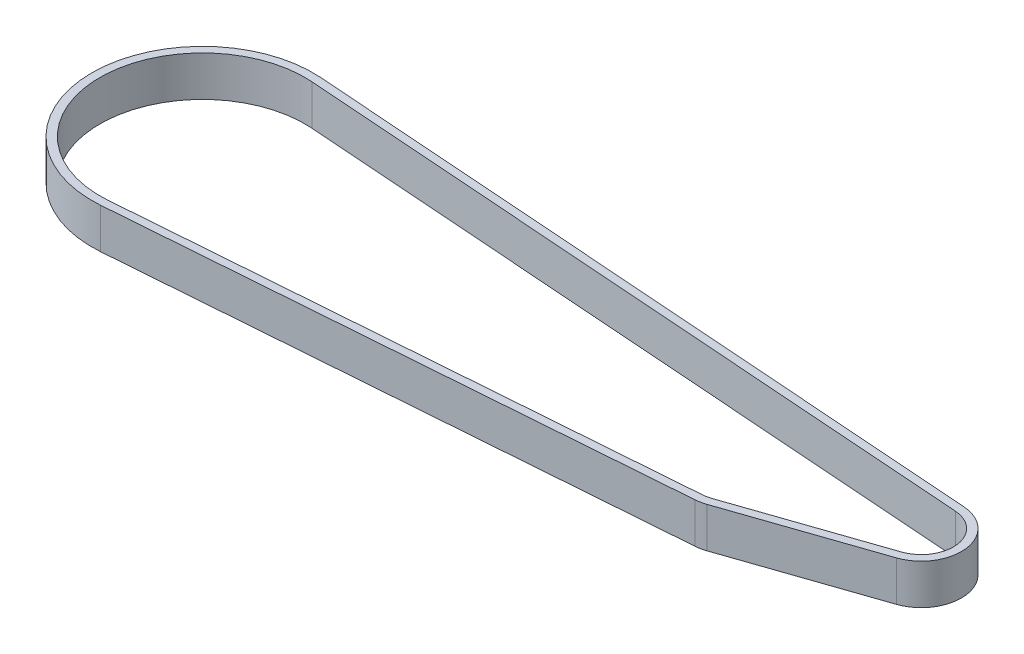
SolidWorks part; units mm, degrees
ref_plane "Alzado" through (0, 0, 0) normal (1, 0, 0) x (0, 1, 0)
ref_plane "Planta" through (0, 0, 0) normal (0, 0, 1) x (0, 1, 0)
ref_plane "Vista lateral" through (0, 0, 0) normal (0, 1, 0) x (-1, 0, 0)
sketch "Croquis1" plane through (0, 0, 0) normal (0, 1, 0) x (-1, 0, 0)
  line L0 (0, 0) -> (173.5, 0) construction
  line L2 (-0.5745, -7.9392) -> (171.6616, -20.4036)
  line L5 (34.3948, 19.937) -> (171.5635, 30.3963)
  line L6 (34.2427, 21.9312) -> (171.4114, 32.3905)
  line L8 (-0.7189, -9.934) -> (171.5172, -22.3984)
  line L9 (-2.5816, 7.5297) -> (32.4184, 19.5297)
  line L10 (-3.2303, 9.4216) -> (31.7697, 21.4216)
  line L11 (173.5, 0) -> (173.5, 5) construction
  line L12 (173.5, 5) -> (0, 0) construction
  arc A0 (-2.5816, 7.5297) -> (-0.5745, -7.9392) centre (0, 0) ccw
  arc A1 (171.6616, -20.4036) -> (171.5635, 30.3963) centre (173.5, 5) ccw
  arc A4 (34.3948, 19.937) -> (32.4184, 19.5297) centre (35, 12) ccw
  arc A6 (171.5172, -22.3984) -> (171.4114, 32.3905) centre (173.5, 5) ccw
  arc A7 (-3.2303, 9.4216) -> (-0.7189, -9.934) centre (0, 0) ccw
  arc A8 (34.2427, 21.9312) -> (31.7697, 21.4216) centre (35, 12) ccw
  arc A9 (171.6616, -20.4036) -> (171.5635, 30.3963) centre (173.5, 5) ccw construction
  dimension "D1" = 15.92
  dimension "D2" = 50.94
  dimension "D5" = 7.96
  dimension "D6" = 35
  dimension "D7" = 12
  dimension "D3" = 173.5
  dimension "D8" = 5
  dimension "D4" = 2
extrude "Saliente-Extruir1" add sketch "Croquis1" along normal mid plane 10
equation "\"Dp1\"=15.92"
equation "\"Dp2\"= 50.94"
equation "\"Lp\"= 455"
equation "\"e\"= 1"
equation "\"D1@Croquis1\"=\"Dp1\""
equation "\"D2@Croquis1\"=\"Dp2\""
equation "\"B\"= 10"
equation "\"D1@Saliente-Extruir1\"=\"B\""
equation "\"Dp_tensor\"=15.92"
equation "\"D5@Croquis1\"=\"Dp_tensor\"/2"
equation "\"x_tensora\"=35"
equation "\"D6@Croquis1\"=\"x_tensora\""
equation "\"y_tensora\"=12"
equation "\"D7@Croquis1\"=\"y_tensora\""
